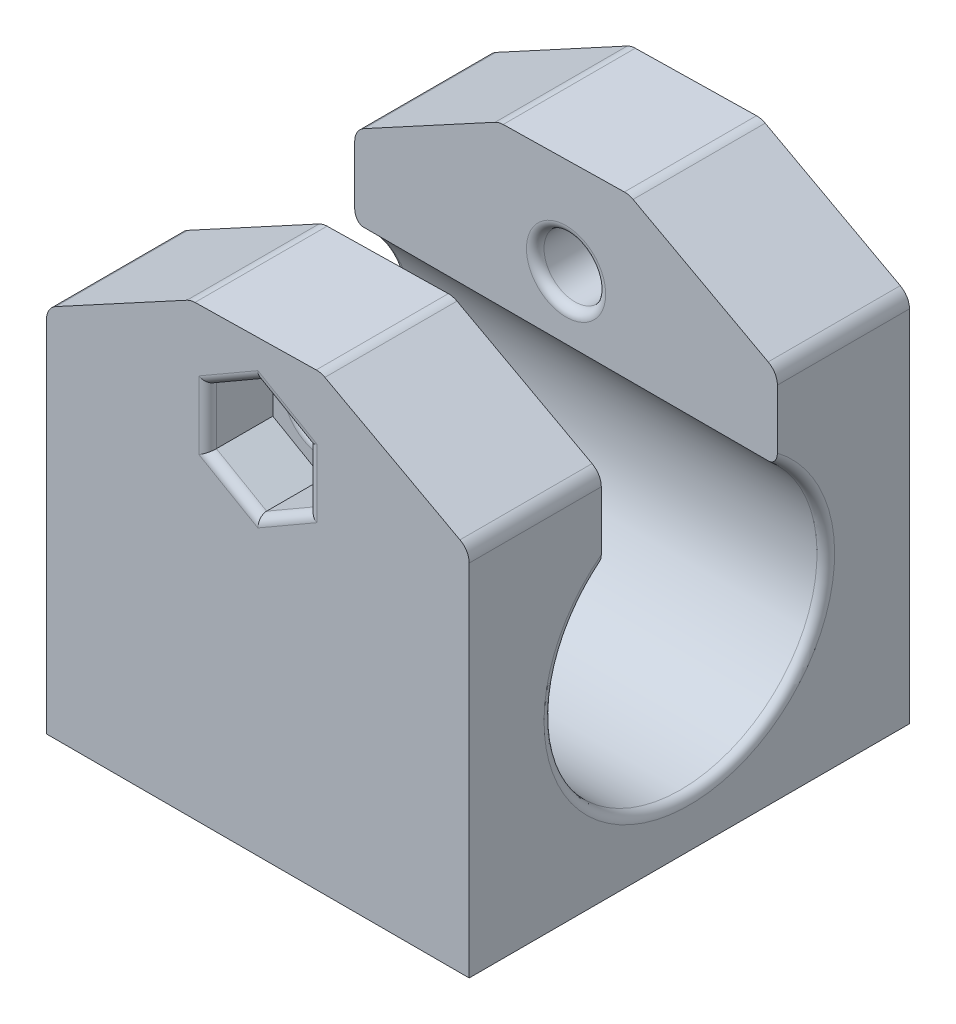
SolidWorks part; units mm, degrees
ref_plane "Front Plane" through (0, 0, 0) normal (0, 0, 1) x (1, 0, 0)
ref_plane "Top Plane" through (0, 0, 0) normal (0, 1, 0) x (1, 0, 0)
ref_plane "Right Plane" through (0, 0, 0) normal (1, 0, 0) x (0, 0, -1)
sketch "Sketch1" plane through (0, 0, 0) normal (0, 1, 0) x (1, 0, 0)
  line L1 (-13.6, 9.9) -> (10.4, 9.9)
  line L2 (-13.6, 9.9) -> (-13.6, -15.1)
  line L3 (-13.6, -15.1) -> (10.4, -15.1)
  line L4 (10.4, 9.9) -> (10.4, -15.1)
  dimension "D1" = 25
  dimension "D2" = 24
extrude "Boss-Extrude1" add sketch "Sketch1" along normal blind 21 contours L1 L4 L3 L2
sketch "Sketch2" plane through (10.4, 0, 0) normal (1, 0, 0) x (0, 0, -1)
  line L0 (9.9, 21) -> (9.9, 0) construction
  line L2 (9.9, 10.5) -> (-15.1, 10.5) construction
  line L3 (-15.1, 21) -> (-15.1, 0) construction
  line L4 (9.9, 21) -> (-15.1, 21) construction
  line L6 (-2.6, 21) -> (-2.6, 0) construction
  line L7 (9.9, 0) -> (-15.1, 0) construction
  circle A0 centre (-2.6, 10.5) radius 7.75
  dimension "D1" = 10.5
  dimension "D3" = 15.5
extrude "Cut-Extrude1" cut sketch "Sketch2" against normal through all
sketch "Sketch3" plane through (10.4, 0, 0) normal (1, 0, 0) x (0, 0, -1)
  line L0 (9.9, 21) -> (-15.1, 21) construction
  line L1 (-7.6, 21) -> (2.4, 21)
  line L2 (-7.6, 21) -> (-7.6, 16.4214)
  line L3 (-7.6, 16.4214) -> (2.4, 16.4214)
  line L4 (2.4, 21) -> (2.4, 16.4214)
  circle A0 centre (-2.6, 10.5) radius 7.75 construction
  dimension "D1" = 10
extrude "Cut-Extrude2" cut sketch "Sketch3" against normal through all
fillet "Fillet4" radius 0.5 2 edges at (-13.6, 2.75, 2.6) (10.4, 2.75, 2.6)
sketch "Sketch4" plane through (0, 21, 0) normal (0, 1, 0) x (1, 0, 0)
  line L1 (10.4, 2.4) -> (-13.6, 2.4)
  line L2 (10.4, 2.4) -> (10.4, 9.9)
  line L3 (10.4, 9.9) -> (-13.6, 9.9)
  line L4 (-13.6, 2.4) -> (-13.6, 9.9)
extrude "Boss-Extrude2" add sketch "Sketch4" along normal blind 6.5
sketch "Sketch5" plane through (0, 0, -9.9) normal (0, 0, -1) x (-1, 0, 0)
  line L0 (13.6, 27.5) -> (1.6, 27.5)
  line L1 (-10.4, 27.5) -> (13.6, 27.5) construction
  line L3 (-10.4, 27.5) -> (-10.4, 0) construction
  line L4 (-10.4, 21) -> (1.6, 27.5)
  line L6 (13.6, 27.5) -> (13.6, 0) construction
  line L7 (13.6, 21) -> (1.6, 27.5)
  line L8 (-10.4, 27.5) -> (1.6, 27.5)
  line L9 (13.6, 21) -> (13.6, 27.5)
  line M3 (13.6, 27.5) -> (-10.4, 27.5)
  line M4 (-10.4, 27.5) -> (-10.4, 0)
  dimension "D1" = 13.6473
  dimension "D2" = 13.6473
sketch "Sketch6" plane through (0, 21, 0) normal (0, 1, 0) x (1, 0, 0)
  line L1 (-13.6, -7.6) -> (10.4, -7.6)
  line L2 (-13.6, -7.6) -> (-13.6, -15.1)
  line L3 (-13.6, -15.1) -> (10.4, -15.1)
  line L4 (10.4, -7.6) -> (10.4, -15.1)
extrude "Boss-Extrude3" add sketch "Sketch6" along normal blind 6.5
extrude "Cut-Extrude5" cut sketch "Sketch5" against normal through all contours L4 M4 M3
sketch "Sketch13" plane through (0, 0, -9.9) normal (0, 0, -1) x (-1, 0, 0)
  line L0 (1.6, 27.5) -> (13.6, 20.9944)
  line L1 (13.6, 27.5) -> (13.6, 0) construction
  line L2 (13.6, 20.9944) -> (13.6, 27.5)
  line L3 (13.6, 27.5) -> (1.6, 27.5)
  dimension "D1" = 13.65
extrude "Cut-Extrude6" cut sketch "Sketch13" against normal through all
sketch "Sketch14" plane through (0, 0, -9.9) normal (0, 0, -1) x (-1, 0, 0)
  line L0 (-1.9751, 25.5635) -> (1.6, 27.5)
  line L1 (1.6, 25.5) -> (5.4141, 25.4323)
  line L2 (1.6, 27.5) -> (13.6, 20.9944) construction
  line L3 (1.6, 25.5) -> (-1.9751, 25.5635)
  line L4 (-10.4, 21) -> (1.6, 27.5) construction
  line L5 (1.6, 27.5) -> (5.4141, 25.4323)
  dimension "D1" = 3.5751
  dimension "D2" = 3.8141
extrude "Cut-Extrude7" cut sketch "Sketch14" against normal through all
sketch "Sketch15" plane through (0, 0, -9.9) normal (0, 0, -1) x (-1, 0, 0)
  line L0 (-1.9751, 25.5635) -> (5.4141, 25.4323) construction
  line L2 (-10.4, 21) -> (-10.4, 0) construction
  circle A0 centre (1.6, 19.9991) radius 1.75
  dimension "D1" = 3.5
  dimension "D2" = 5.5
  dimension "D3" = 12
extrude "Cut-Extrude8" cut sketch "Sketch15" against normal through all
fillet "Fillet5" radius 0.5 1 edges at (-3.35, 19.9991, -9.9)
sketch "Sketch16" plane through (0, 0, -9.9) normal (0, 0, -1) x (-1, 0, 0)
  line L0 (-1.9751, 25.5635) -> (5.4141, 25.4323) construction
  circle A0 centre (1.6, 19.9992) radius 3
  point P2 (1.7195, 25.4979)
  dimension "D1" = 12
  dimension "D3" = 6
  dimension "D2" = 5.5
extrude "Cut-Extrude9" cut sketch "Sketch16" against normal blind 3.7
fillet "Fillet6" radius 0.5 2 edges at (-4.6, 19.9992, -9.9) (-3.35, 19.9991, -6.2)
sketch "Sketch17" plane through (0, 0, 15.1) normal (0, 0, 1) x (1, 0, 0)
  line L0 (1.9751, 25.5635) -> (-5.4141, 25.4323) construction
  line L1 (-4.45, 21.6446) -> (-4.45, 18.3537)
  line L2 (-4.45, 18.3537) -> (-1.6, 16.7082)
  line L3 (-1.6, 16.7082) -> (1.25, 18.3537)
  line L4 (1.25, 18.3537) -> (1.25, 21.6446)
  line L5 (1.25, 21.6446) -> (-1.6, 23.29)
  line L6 (-1.6, 23.29) -> (-4.45, 21.6446)
  circle A0 centre (-1.6, 19.9991) radius 2.85 construction
  dimension "D3" = 5.7
  dimension "D1" = 5.5
  dimension "D2" = 12
extrude "Cut-Extrude10" cut sketch "Sketch17" against normal blind 3.7
fillet "Fillet7" radius 0.5 6 edges at (-0.175, 17.531, 15.1) (1.25, 19.9991, 15.1) (-0.175, 22.4673, 15.1) (-3.025, 22.4673, 15.1) (-4.45, 19.9991, 15.1) (-3.025, 17.531, 15.1)
fillet "Fillet8" radius 0.5 1 edges at (0.15, 19.9991, 11.4)
ref_plane "Plane1" through (-1.6, 23.8674, 15.1) normal (0, -1, 0) x (-1, 0, 0)
sketch "Sketch19" plane through (0, 0, 11.4) normal (0, 0, 1) x (1, 0, 0)
ref_plane "Plane2" through (-1.6, 16.1309, 15.1) normal (0, -1, 0) x (-1, 0, 0)
fillet "Fillet9" radius 0.5 1 edges at (-1.6, 21.7491, -2.4)
fillet "Fillet10" radius 0.5 1 edges at (-1.6, 18.2491, 7.6)
fillet "Fillet14" radius 1 8 edges at (-13.6, 20.9944, -6.15) (-13.6, 20.9944, 11.35) (1.9751, 25.5635, 11.35) (-5.4141, 25.4323, 11.35) (-5.4141, 25.4323, -6.15) (1.9751, 25.5635, -6.15) (10.4, 21, -6.15) (10.4, 21, 11.35)
